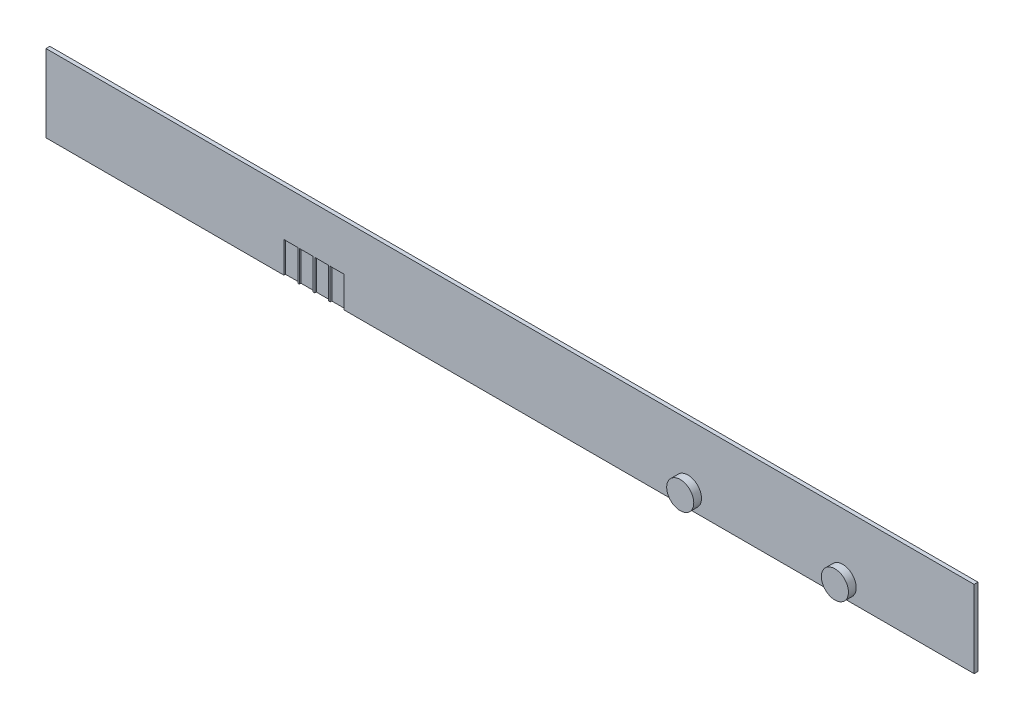
SolidWorks part; units mm, degrees
ref_plane "Front Plane" through (0, 0, 0) normal (0, 0, 1) x (1, 0, 0)
ref_plane "Top Plane" through (0, 0, 0) normal (0, 1, 0) x (1, 0, 0)
ref_plane "Right Plane" through (0, 0, 0) normal (1, 0, 0) x (0, 0, -1)
sketch "Sketch1" plane through (0, 0, 0) normal (0, 0, 1) x (1, 0, 0)
  line L1 (-60, -5) -> (60, -5)
  line L2 (-60, -5) -> (-60, 5)
  line L3 (-60, 5) -> (60, 5)
  line L4 (60, -5) -> (60, 5)
  line L5 (-60, -5) -> (60, 5) construction
  line L6 (-60, 5) -> (60, -5) construction
  point P0 (0, 0)
  dimension "D1" = 120
  dimension "D2" = 10
extrude "Boss-Extrude1" add sketch "Sketch1" along normal blind 0.5
sketch "Guide" plane through (0, 0, 0.5) normal (0, 0, 1) x (1, 0, 0)
  line L0 (-60, -3) -> (-27, -3) construction
  line L1 (-60, 0.5292) -> (60, 0.5292) construction
  line L2 (-27, -3) -> (23, -3) construction
  line L3 (23, -3) -> (43, -3) construction
  line L4 (-52.2688, -3) -> (-52.2688, -5) construction
  line L5 (-60, -5) -> (60, -5) construction
  line L6 (-60, 5) -> (-60, -5) construction
  line L7 (60, -5) -> (60, 5) construction
  dimension "D1" = 2
  dimension "D2" = 50
  dimension "D3" = 20
sketch "Jacks" plane through (0, 0, 0.5) normal (0, 0, 1) x (1, 0, 0)
  circle A0 centre (23, -3) radius 1.75
  circle A1 centre (43, -3) radius 1.75
  dimension "D1" = 3.5
extrude "Boss-Extrude2" add sketch "Jacks" along normal blind 1
sketch "usb port" plane through (0, 0, 0.5) normal (0, 0, 1) x (1, 0, 0)
  line L1 (-29.25, -1) -> (-24.75, -1) construction
  line L2 (-29.25, -1) -> (-29.25, -5) construction
  line L3 (-29.25, -5) -> (-24.75, -5) construction
  line L4 (-24.75, -1) -> (-24.75, -5) construction
  line L5 (-29.25, -1) -> (-24.75, -5) construction
  line L6 (-29.25, -5) -> (-24.75, -1) construction
  line L7 (-24.75, -1) -> (-26.55, -1) construction
  line L8 (-24.75, -1) -> (-24.75, -5) construction
  line L9 (-24.75, -5) -> (-26.55, -5) construction
  line L10 (-26.55, -1) -> (-26.55, -5) construction
  line L11 (-29.25, -5) -> (-27.45, -5)
  line L12 (-29.25, -5) -> (-29.25, -1)
  line L13 (-29.25, -1) -> (-27.45, -1)
  line L14 (-27.45, -5) -> (-27.45, -1)
  point P0 (-27, -3)
  dimension "D1" = 4
  dimension "D2" = 4.5
  dimension "D3" = 1.8
extrude "Cut-Extrude2" cut sketch "usb port" against normal blind 0.2
pattern_linear "LPattern1" count 4 spacing 2 along (1, 0, 0) of "Cut-Extrude2"
